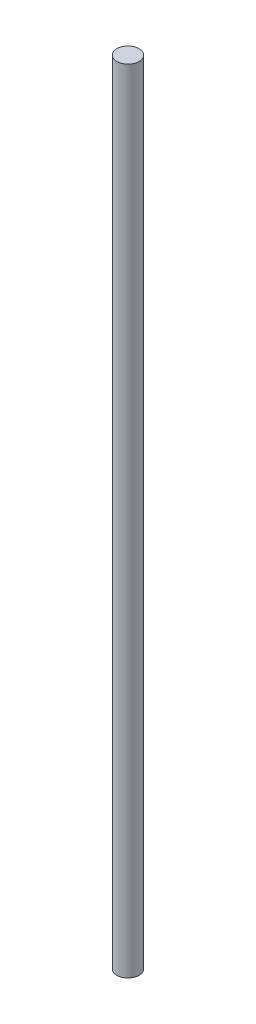
SolidWorks part; units mm, degrees
ref_plane "Front Plane" through (0, 0, 0) normal (0, 0, 1) x (1, 0, 0)
ref_plane "Top Plane" through (0, 0, 0) normal (0, 1, 0) x (1, 0, 0)
ref_plane "Right Plane" through (0, 0, 0) normal (1, 0, 0) x (0, 0, -1)
ref_plane "Plane1"
sketch "Sketch1" plane through (0, 0, 0) normal (0, 1, 0) x (-1, 0, 0)
  circle A0 centre (0, 0) radius 5
  dimension "D1" = 10
extrude "Extrusion1" add sketch "Sketch1" along normal blind 355.6
